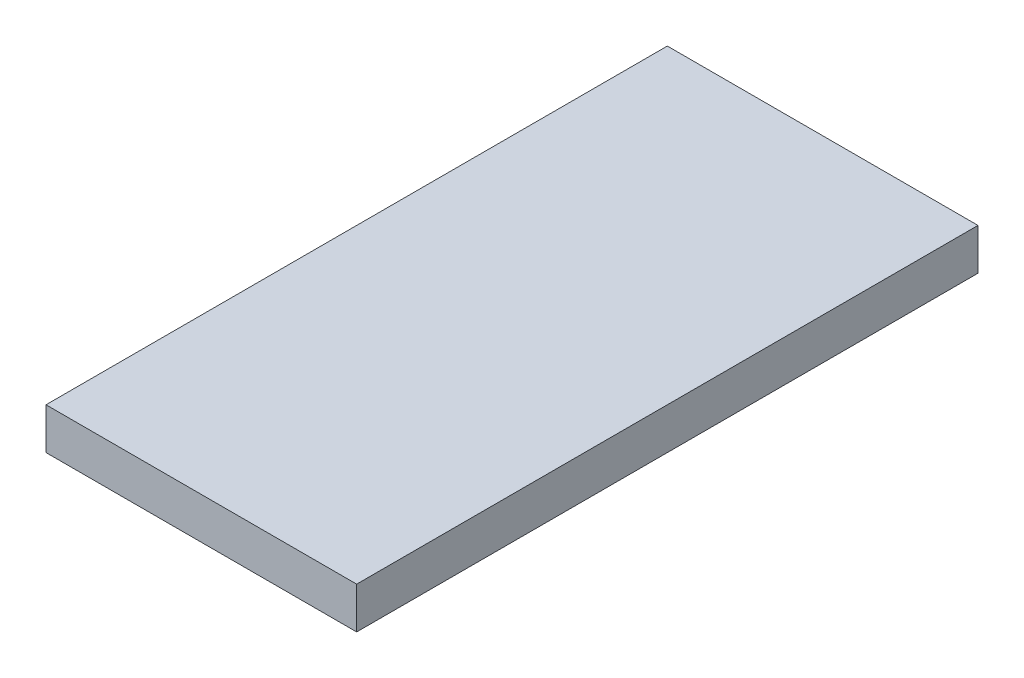
SolidWorks part; units mm, degrees
material "Thornel Mat VMA"
ref_plane "Front Plane" through (0, 0, 0) normal (0, 0, 1) x (1, 0, 0)
ref_plane "Top Plane" through (0, 0, 0) normal (0, 1, 0) x (1, 0, 0)
ref_plane "Right Plane" through (0, 0, 0) normal (1, 0, 0) x (0, 0, -1)
sketch "Sketch1" plane through (0, 0, 0) normal (0, 1, 0) x (1, 0, 0)
  line L1 (0.75, -1.5) -> (-0.75, -1.5)
  line L2 (0.75, -1.5) -> (0.75, 1.5)
  line L3 (0.75, 1.5) -> (-0.75, 1.5)
  line L4 (-0.75, -1.5) -> (-0.75, 1.5)
  line L5 (0, 1.5) -> (0, -1.5) construction
  line L6 (0.75, 0) -> (-0.75, 0) construction
  point P0 (0, 0)
  dimension "D1" = 3
  dimension "D2" = 1.5
extrude "Boss-Extrude1" add sketch "Sketch1" along normal mid plane 0.2
sketch "Sketch3" plane through (0, 0, 0) normal (1, 0, 0) x (0, 0, -1)
  line L0 (1.5, 0.025) -> (1.5, -0.025)
  line L1 (1.5, 0.1) -> (1.5, -0.1) construction
  line L2 (1.8025, 0.0065) -> (1.7964, -0.0431)
  line L3 (1.5, 0.025) -> (1.6056, 0.025) construction
  line L4 (1.5, 0) -> (1.6503, 0) construction
  line L5 (1.7964, -0.0431) -> (1.2433, -4.5474) construction
  line L6 (1.7994, -0.0183) -> (1.6503, 0) construction
  arc A0 (1.5, -0.025) -> (1.7964, -0.0431) centre (1.5, -2.4571) cw
  arc A1 (1.5, 0.025) -> (1.8025, 0.0065) centre (1.5, -2.4571) cw
  arc A2 (1.5, 0) -> (1.7994, -0.0183) centre (1.5, -2.4571) cw construction
  point P12 (1.6515, 0.0204)
  point P14 (1.6485, -0.0295)
  dimension "D1" = 0.05
  dimension "D2" = 0.05
  dimension "D3" = 0.3
  dimension "D4" = 7
  dimension "D5" = 0.05
extrude "Boss-Extrude3" [suppressed] add sketch "Sketch3" along normal mid plane 1.45
sketch "Sketch4" [suppressed] plane through (0, 0, 0) normal (1, 0, 0) x (0, 0, -1)
  line L0 (1.5972, -0.0301) -> (1.6025, 0.0196) construction
  line L1 (1.5894, -0.1047) -> (1.6103, 0.0942)
  line L2 (1.6103, 0.0942) -> (4.5939, -0.2194)
  line L3 (4.5939, -0.2194) -> (4.573, -0.4183)
  line L4 (4.573, -0.4183) -> (1.5894, -0.1047)
  point P7 (1.5999, -0.0052)
  point P8 (1.5999, -0.0052)
  dimension "D1" = 0.2
  dimension "D2" = 3
extrude "Boss-Extrude4" [suppressed] add sketch "Sketch4" along normal mid plane 1.5
sketch "Sketch6" [suppressed] plane through (0, 0, 0) normal (1, 0, 0) x (0, 0, -1)
  line L0 (4.586, -0.294) -> (4.5808, -0.3437)
  line L2 (4.6874, -0.31) -> (4.677, -0.3589)
  line L3 (4.586, -0.294) -> (1.5839, 0.0216) construction
  line L4 (4.5834, -0.3188) -> (4.6332, -0.3241) construction
  line L5 (4.677, -0.3589) -> (4.0154, -3.4716) construction
  line L6 (4.6822, -0.3345) -> (4.6332, -0.3241) construction
  line L7 (4.573, -0.4183) -> (4.5939, -0.2194) construction
  arc A0 (4.5808, -0.3437) -> (4.677, -0.3589) centre (4.4836, -1.269) cw
  arc A1 (4.586, -0.294) -> (4.6874, -0.31) centre (4.4836, -1.269) cw
  arc A2 (4.5834, -0.3188) -> (4.6822, -0.3345) centre (4.4836, -1.269) cw construction
  point P12 (4.6369, -0.3007)
  point P14 (4.6291, -0.35)
  point P24 (4.5834, -0.3188)
  dimension "D1" = 0.05
  dimension "D2" = 0.05
  dimension "D3" = 0.3
  dimension "D4" = 7
  dimension "D5" = 0.05
extrude "Boss-Extrude5" [suppressed] add sketch "Sketch6" along normal mid plane 1.45
sketch "Sketch7" plane through (0, 0, 1.5) normal (0, 0, 1) x (1, 0, 0)
  line L0 (-0.75, 0) -> (0.75, 0) construction
  line L1 (-0.75, 0.1) -> (-0.75, -0.1) construction
  line L2 (0.75, 0.1) -> (0.75, -0.1) construction
sketch "Sketch8" [suppressed] plane through (0, -0.9667, -4.5478) normal (0, -0.2079, -0.9781) x (-1, 0, 0)
  line L0 (-0.975, 0.6463) -> (0.975, 0.6463) construction
  line L1 (-0.975, 0.6213) -> (-0.975, 0.6713) construction
  line L2 (0.975, 0.6213) -> (0.975, 0.6713) construction
equation "\"cf_length\"= 3mm"
equation "\"cf_width\" = 1.5mm"
equation "\"cf_thickness\"= .2mm"
equation "\"kap_length\" = .3mm"
equation "\"kap_depth\"= .05mm"
equation "\"kap_curvature\"= 7deg'total angle of curvature for kapton hinge"
equation "\"D1@Sketch1\"=\"cf_length\""
equation "\"D2@Sketch1\"=\"cf_width\""
equation "\"D1@Boss-Extrude1\"=\"cf_thickness\""
equation "\"D1@Sketch3\"=\"kap_depth\""
equation "\"D2@Sketch3\"=\"kap_depth\""
equation "\"D3@Sketch3\"=\"kap_length\""
equation "\"D4@Sketch3\"=\"kap_curvature\""
equation "\"D5@Sketch3\"=\"kap_depth\""
equation "\"D1@Boss-Extrude3\"=\"cf_width\"-\"kap_depth\""
equation "\"D1@Sketch4\"=\"cf_thickness\""
equation "\"D2@Sketch4\"=\"cf_length\""
equation "\"D1@Boss-Extrude4\"=\"cf_width\""
equation "\"D4@Sketch6\"=\"kap_curvature\""
equation "\"D5@Sketch6\"=\"kap_depth\""
equation "\"D2@Sketch6\"=\"kap_depth\""
equation "\"D3@Sketch6\"=\"kap_length\""
equation "\"D1@Boss-Extrude5\"=\"cf_width\"-\"kap_depth\""
